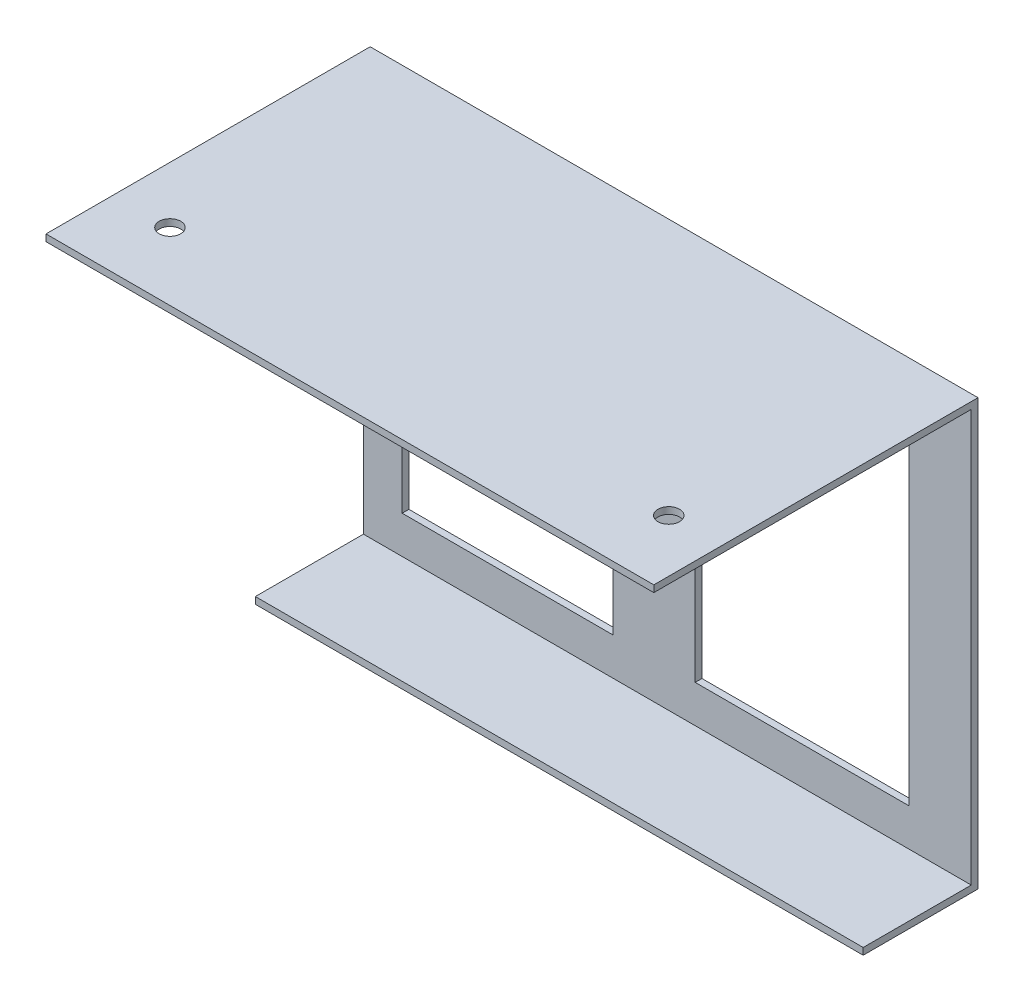
SolidWorks part; units mm, degrees
ref_plane "前视基准面" through (0, 0, 0) normal (0, 0, 1) x (1, 0, 0)
ref_plane "上视基准面" through (0, 0, 0) normal (0, 1, 0) x (1, 0, 0)
ref_plane "右视基准面" through (0, 0, 0) normal (1, 0, 0) x (0, 0, -1)
sketch "草图1" plane through (0, 0, 0) normal (0, 0, 1) x (1, 0, 0)
  line L1 (0, 0) -> (90, 0)
  line L2 (0, 0) -> (0, 63)
  line L3 (0, 63) -> (90, 63)
  line L4 (90, 0) -> (90, 63)
  dimension "D1" = 63
  dimension "D2" = 90
extrude "凸台-拉伸1" add sketch "草图1" along normal blind 1
sketch "草图2" plane through (0, 0, 1) normal (0, 0, 1) x (1, 0, 0)
  line L2 (90, 0) -> (90, 63) construction
  line L3 (0, 63) -> (90, 63)
  line L4 (0, 63) -> (0, 62)
  line L5 (0, 62) -> (90, 62)
  line L6 (90, 63) -> (90, 62)
  line L7 (0, 63) -> (0, 0) construction
  line L8 (0, 1) -> (90, 1)
  line L9 (0, 1) -> (0, 0)
  line L10 (0, 0) -> (90, 0)
  line L11 (90, 1) -> (90, 0)
  dimension "D1" = 1
  dimension "D2" = 1
extrude "凸台-拉伸2" add sketch "草图2" along normal blind 47
sketch "草图3" plane through (0, 0, 48) normal (0, 0, 1) x (1, 0, 0)
  line L0 (90, 1) -> (0, 1) construction
  line L1 (0, 0) -> (101.3676, 0)
  line L2 (0, 0) -> (0, 1)
  line L3 (0, 1) -> (101.3676, 1)
  line L4 (101.3676, 0) -> (101.3676, 1)
extrude "切除-拉伸1" cut sketch "草图3" against normal blind 31
sketch "草图4" plane through (0, 0, 1) normal (0, 0, 1) x (1, 0, 0)
  line L1 (5.7338, 55.442) -> (36.9858, 55.442)
  line L2 (5.7338, 55.442) -> (5.7338, 6.5521)
  line L3 (5.7338, 6.5521) -> (36.9858, 6.5521)
  line L4 (36.9858, 55.442) -> (36.9858, 6.5521)
  line L5 (49.1245, 55.442) -> (80.7788, 55.442)
  line L6 (49.1245, 55.442) -> (49.1245, 6.5521)
  line L7 (49.1245, 6.5521) -> (80.7788, 6.5521)
  line L8 (80.7788, 55.442) -> (80.7788, 6.5521)
extrude "切除-拉伸2" cut sketch "草图4" against normal blind 31
sketch "草图5" plane through (0, 62, 0) normal (0, -1, 0) x (1, 0, 0)
  line L0 (0, 38) -> (50000, 38) construction
  line L3 (0, 48) -> (90, 48) construction
  circle A0 centre (8.3582, 38) radius 1.6
  circle A1 centre (82.2052, 38) radius 1.6
  dimension "D2" = 3.2
  dimension "D3" = 3.2
  dimension "D1" = 10
extrude "切除-拉伸3" cut sketch "草图5" against normal blind 31
